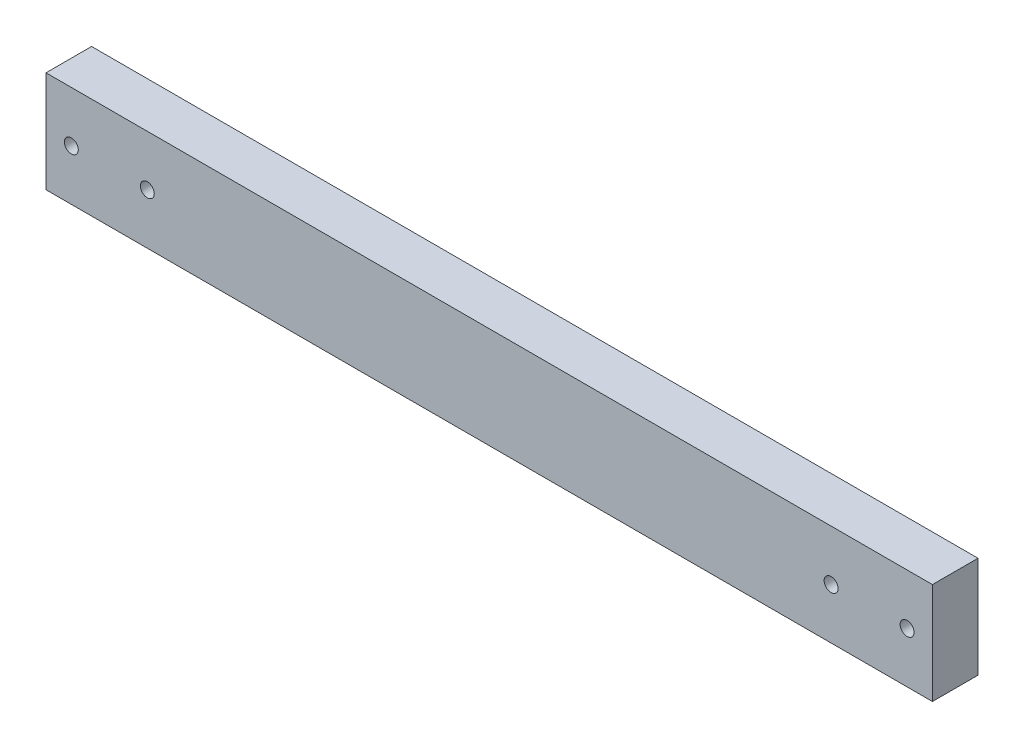
SolidWorks part; units mm, degrees
ref_plane "Front Plane" through (0, 0, 0) normal (0, 0, 1) x (1, 0, 0)
ref_plane "Top Plane" through (0, 0, 0) normal (0, 1, 0) x (1, 0, 0)
ref_plane "Right Plane" through (0, 0, 0) normal (1, 0, 0) x (0, 0, -1)
sketch "Sketch1" plane through (0, 0, 0) normal (0, 0, 1) x (1, 0, 0)
  line L1 (0, 0) -> (350, 0)
  line L2 (0, 0) -> (0, 40)
  line L3 (0, 40) -> (350, 40)
  line L4 (350, 0) -> (350, 40)
  dimension "D1" = 40
  dimension "D2" = 350
extrude "Boss-Extrude1" add sketch "Sketch1" along normal blind 18
sketch "Sketch2" plane through (0, 0, 18) normal (0, 0, 1) x (1, 0, 0)
  line L0 (350, 40) -> (0, 40) construction
  line L1 (0, 40) -> (0, 0) construction
  line L2 (350, 0) -> (350, 40) construction
  circle A0 centre (10, 20) radius 2.75
  circle A1 centre (40, 20) radius 2.75
  circle A2 centre (310, 20) radius 2.75
  circle A3 centre (340, 20) radius 2.75
  dimension "D1" = 5.5
  dimension "D2" = 5.5
  dimension "D3" = 5.5
  dimension "D4" = 5.5
  dimension "D5" = 30
  dimension "D6" = 20
  dimension "D7" = 0
  dimension "D8" = 10
  dimension "D9" = 30
  dimension "D10" = 20
  dimension "D11" = 20
  dimension "D12" = 10
extrude "Cut-Extrude1" cut sketch "Sketch2" against normal blind 20
